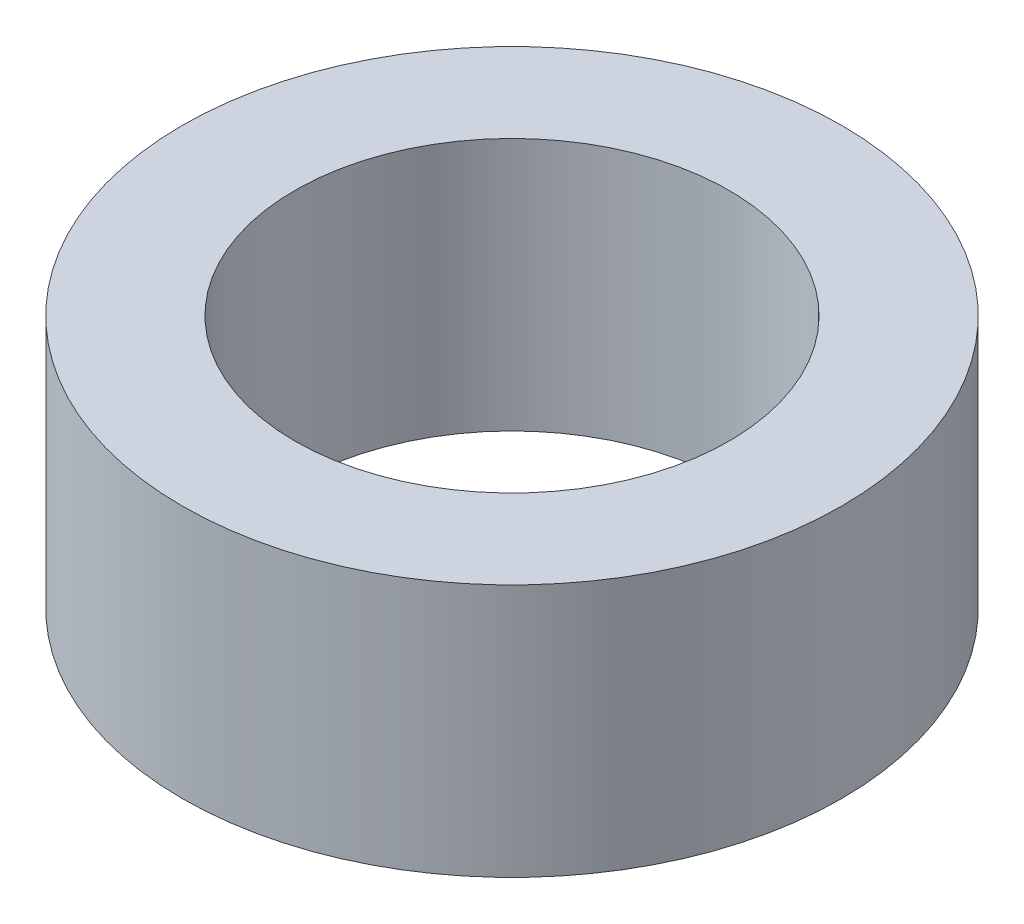
SolidWorks part; units mm, degrees
ref_plane "Front Plane" through (0, 0, 0) normal (0, 0, 1) x (1, 0, 0)
ref_plane "Top Plane" through (0, 0, 0) normal (0, 1, 0) x (1, 0, 0)
ref_plane "Right Plane" through (0, 0, 0) normal (1, 0, 0) x (0, 0, -1)
sketch "Sketch1" plane through (0, 0, 0) normal (0, 1, 0) x (1, 0, 0)
  circle A0 centre (0, 0) radius 3.675
  circle A1 centre (0, 0) radius 5.58
  dimension "D1" = 11.16
  dimension "D2" = 7.35
extrude "Boss-Extrude1" add sketch "Sketch1" along normal blind 4.2875
